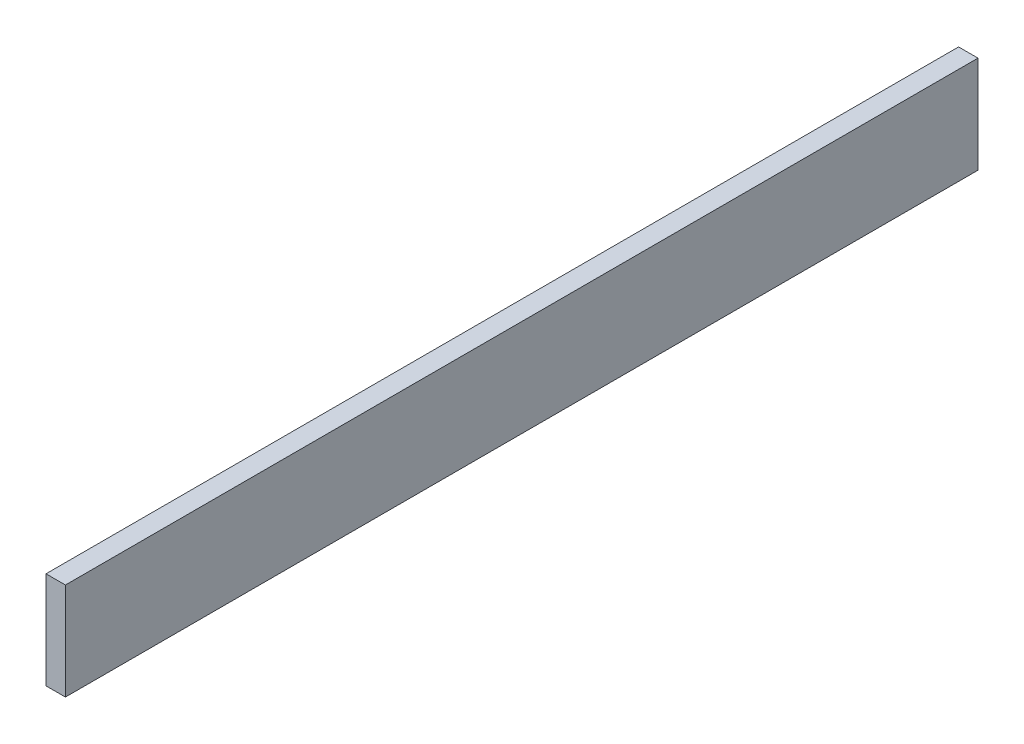
SolidWorks part; units mm, degrees
ref_plane "Front Plane" through (0, 0, 0) normal (0, 0, 1) x (1, 0, 0)
ref_plane "Top Plane" through (0, 0, 0) normal (0, 1, 0) x (1, 0, 0)
ref_plane "Right Plane" through (0, 0, 0) normal (1, 0, 0) x (0, 0, -1)
sketch "Sketch1" plane through (0, 0, 0) normal (1, 0, 0) x (0, 0, -1)
  line L0 (0, 0) -> (470, 0)
  line L1 (470, 0) -> (470, 50)
  line L2 (470, 50) -> (0, 50)
  line L3 (0, 0) -> (0, 50)
  dimension "D1" = 470
  dimension "D2" = 50
extrude "Boss-Extrude1" add sketch "Sketch1" along normal blind 10
